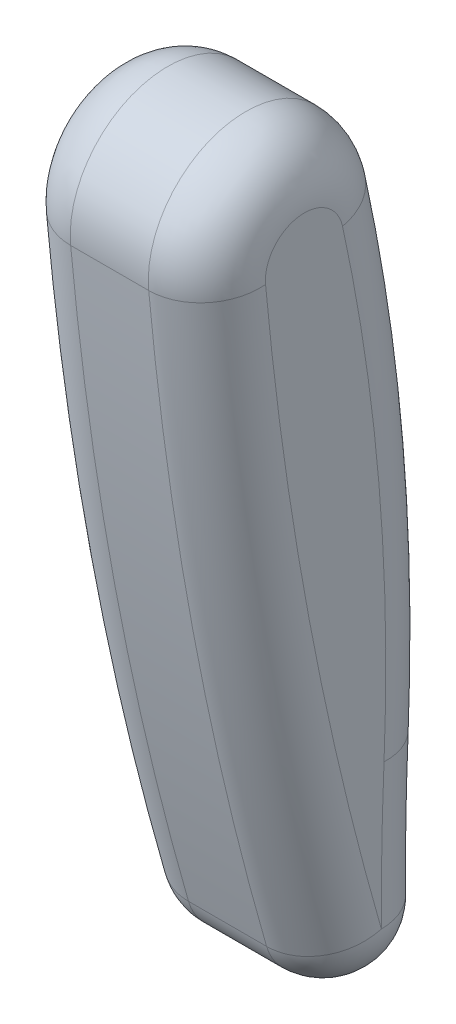
SolidWorks part; units mm, degrees
material "PW90:Mi:0:29:C1:0:1:2:Re:16:"
ref_plane "XY" through (0, 0, 0) normal (0, 0, 1) x (1, 0, 0)
ref_plane "YZ" through (0, 0, 0) normal (0, 1, 0) x (1, 0, 0)
ref_plane "XZ" through (0, 0, 0) normal (1, 0, 0) x (0, 0, -1)
ref_plane "Leg-plane" through (114.3, 0, 0) normal (1, 0, 0) x (0, 0, -1)
sketch "Sketch7" plane through (114.3, 0, 0) normal (1, 0, 0) x (0, 0, -1)
  line L1 (-24.1632, -755.7123) -> (25.9157, -1159.015) construction
  line L2 (0, 432.2232) -> (0, -432.2232) construction
  arc A0 (37.8855, -742.2138) -> (-87.3963, -761.529) centre (-24.1632, -755.7123) ccw
  arc A1 (-10.7018, -1169.5397) -> (64.015, -1158.7778) centre (25.9157, -1159.015) ccw
  arc A2 (-10.7018, -1169.5397) -> (-87.3963, -761.529) centre (2113.1133, -559.109) cw
  arc A3 (37.8855, -742.2138) -> (65.7157, -1067.2864) centre (-1203.0883, -1012.1842) cw
  arc A4 (64.015, -1158.7778) -> (65.7157, -1067.2864) centre (1908.0143, -1147.2947) cw
  dimension "D1" = 406.4
  dimension "D2" = 38.1
  dimension "D3" = 63.5
  dimension "D4" = 1270
  dimension "D5" = 50.8
  dimension "D6" = 2209.8
  dimension "D8" = 1844.0351
  dimension "D7" = 7.078
extrude "Base-Extrude" add sketch "Sketch7" along normal mid plane 127
fillet "Fillet1" radius 38.1
